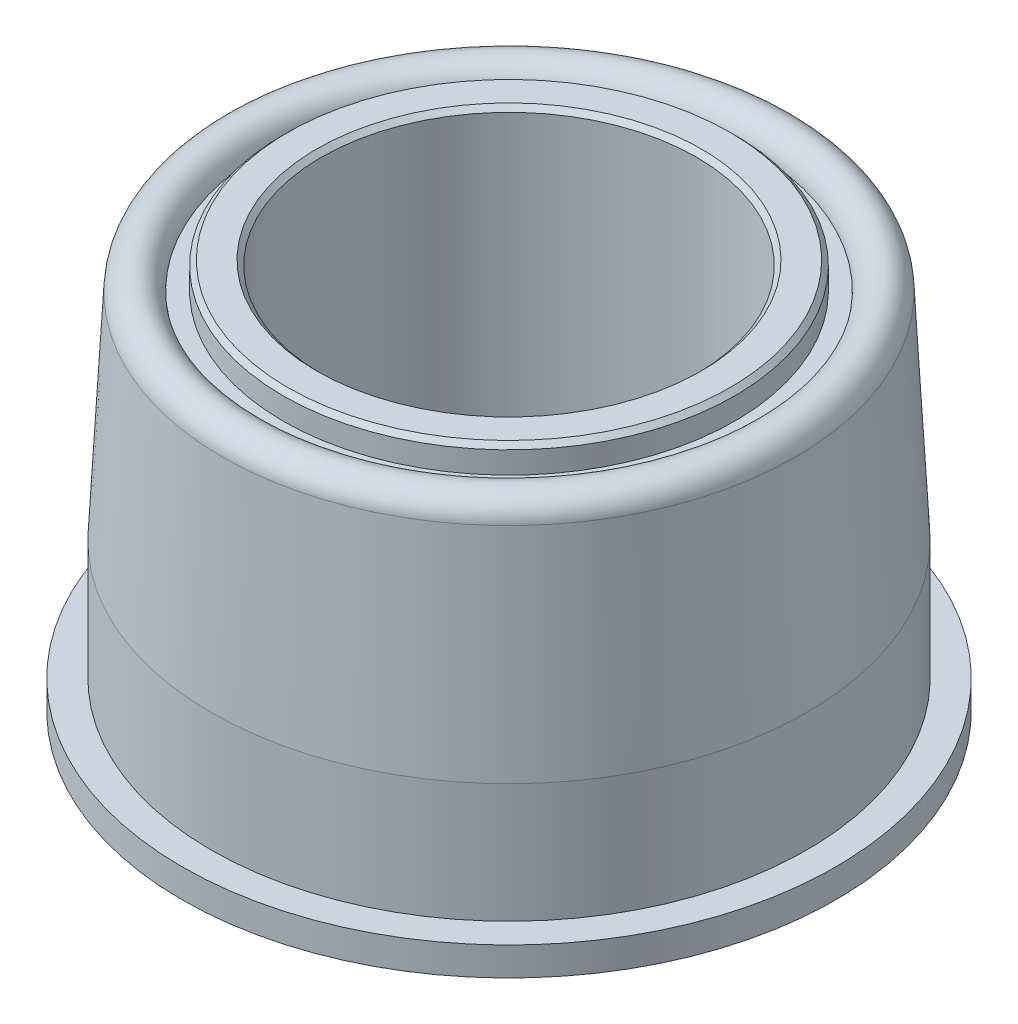
SolidWorks part; units mm, degrees
ref_plane "Front Plane" through (0, 0, 0) normal (0, 0, 1) x (1, 0, 0)
ref_plane "Top Plane" through (0, 0, 0) normal (0, 1, 0) x (1, 0, 0)
ref_plane "Right Plane" through (0, 0, 0) normal (1, 0, 0) x (0, 0, -1)
sketch "Sketch1" plane through (0, 0, 0) normal (0, 0, 1) x (1, 0, 0)
  line L0 (0, 15.2815) -> (0, 0) construction
  line L1 (0, 0) -> (-8.4619, 0) construction
  line L19 (-8.7122, 0.381) -> (-8.7122, 1.143)
  line L20 (-8.7122, 1.143) -> (-7.9375, 1.143)
  line L21 (-7.9375, 1.143) -> (-7.9375, 4.318)
  line L22 (-7.9375, 4.318) -> (-7.6364, 10.0636)
  line L23 (-6.471, 10.0838) -> (-6.0198, 10.0838)
  line L24 (-6.0198, 10.0838) -> (-6.0198, 10.795)
  line L26 (-6.0198, 10.795) -> (-5, 10.795)
  line L28 (-5, 10.795) -> (-5, 0)
  line L30 (-5, 0) -> (-6.0198, 0)
  line L32 (-6.0198, 0) -> (-6.0198, 1.651)
  line L33 (-6.0198, 1.651) -> (-6.4008, 1.651)
  line L34 (-6.4008, 1.651) -> (-6.4008, 0.381)
  line L36 (-6.4008, 0.381) -> (-8.7122, 0.381)
  arc A1 (-7.6364, 10.0636) -> (-6.471, 10.0838) centre (-7.053, 10.033) cw
  dimension "D7" = 9.652
  dimension "D8" = 0.5842
  dimension "D1" = 0.762
  dimension "D2" = 3.937
  dimension "D3" = 7.9375
  dimension "D4" = 10
  dimension "D5" = 17.4244
  dimension "D6" = 10.795
  dimension "D9" = 3
  dimension "D10" = 0.7112
  dimension "D11" = 0.0508
  dimension "D12" = 12.0396
  dimension "D13" = 1.27
  dimension "D14" = 0.381
revolve "Revolve1" add sketch "Sketch1" angle 360 about L0
chamfer "Chamfer1" distance 0.127 angle 45 3 edges at (0, 0, 5) (0, 10.795, 5) (0, 10.795, 6.0198)
